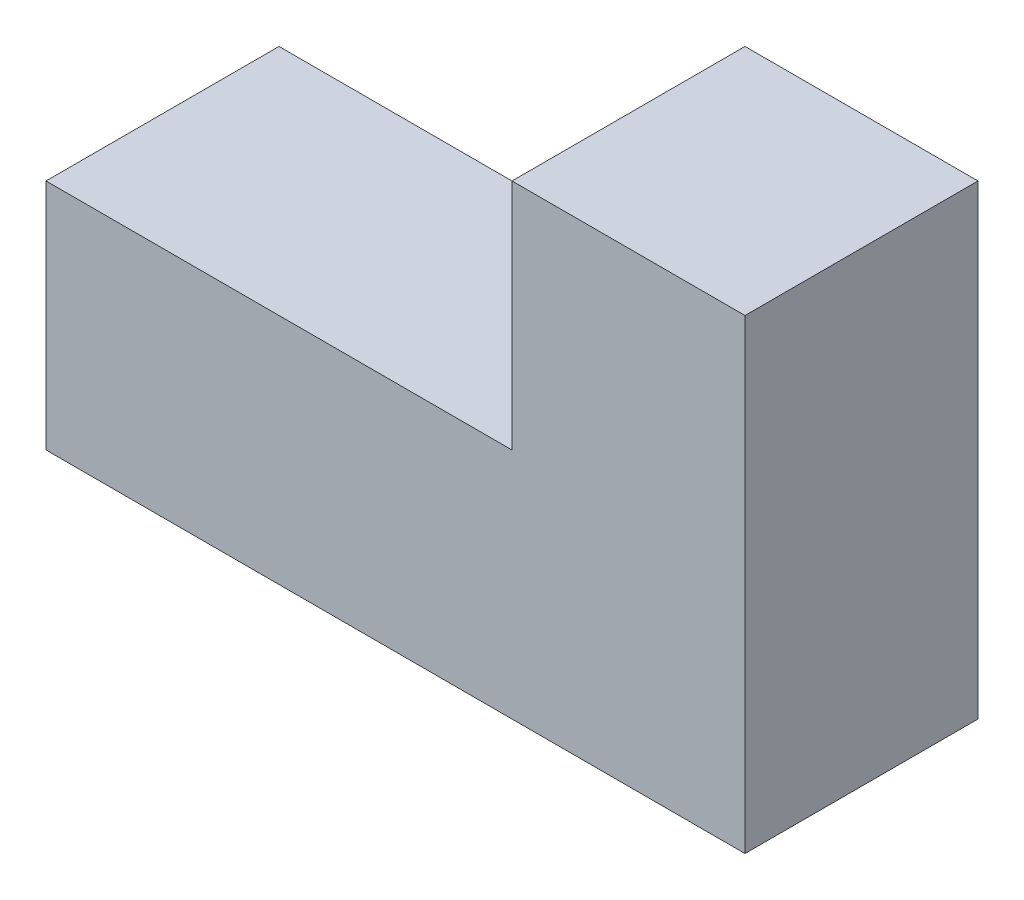
SolidWorks part; units mm, degrees
ref_plane "前基準面" through (0, 0, 0) normal (0, 0, 1) x (1, 0, 0)
ref_plane "上基準面" through (0, 0, 0) normal (0, 1, 0) x (1, 0, 0)
ref_plane "右基準面" through (0, 0, 0) normal (1, 0, 0) x (0, 0, -1)
sketch "草圖1" plane through (0, 0, 0) normal (0, 0, 1) x (1, 0, 0)
  line L0 (0, 0) -> (90, 0)
  line L1 (90, 0) -> (90, -30)
  line L2 (90, -30) -> (0, -30)
  line L3 (0, -30) -> (0, 0)
  dimension "D1" = 90
  dimension "D2" = 30
extrude "填料-伸長1" add sketch "草圖1" along normal blind 30
sketch "草圖2" plane through (0, 0, 0) normal (0, 1, 0) x (1, 0, 0)
  line L0 (90, 0) -> (60, 0)
  line L1 (90, 0) -> (0, 0) construction
  line L2 (60, 0) -> (60, -30)
  line L3 (90, -30) -> (0, -30) construction
  line L4 (60, -30) -> (90, -30)
  line L5 (90, -30) -> (90, 0)
  dimension "D1" = 30
extrude "填料-伸長2" add sketch "草圖2" along normal blind 30
